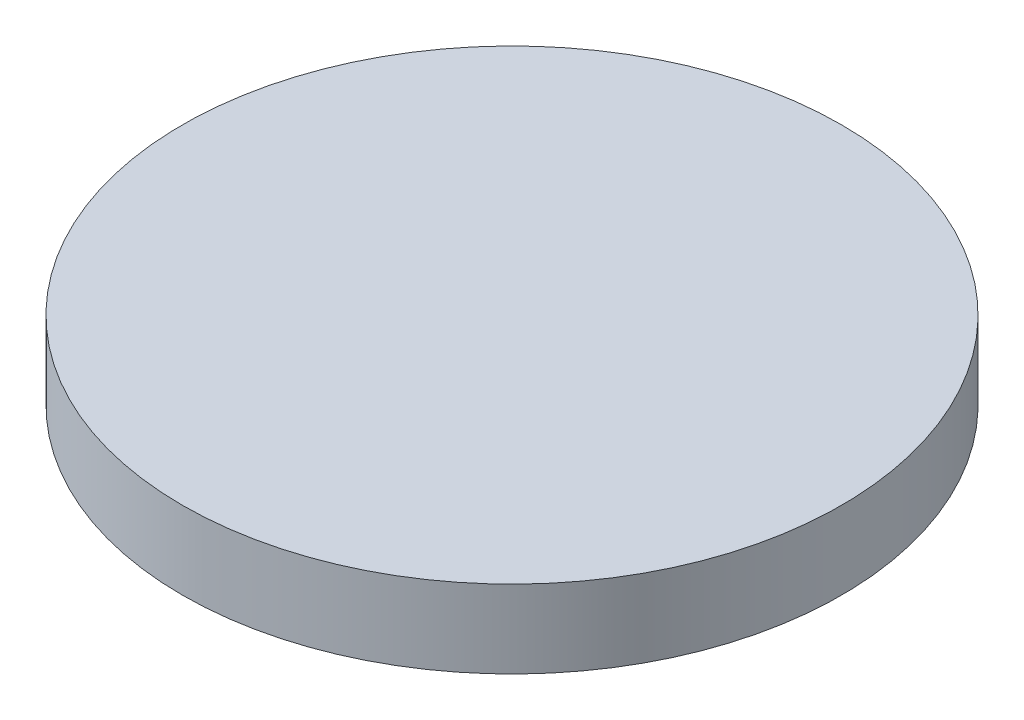
SolidWorks part; units mm, degrees
ref_plane "Front Plane" through (0, 0, 0) normal (0, 0, 1) x (1, 0, 0)
ref_plane "Top Plane" through (0, 0, 0) normal (0, 1, 0) x (1, 0, 0)
ref_plane "Right Plane" through (0, 0, 0) normal (1, 0, 0) x (0, 0, -1)
sketch "Sketch1" plane through (0, 0, 0) normal (0, 1, 0) x (1, 0, 0)
  circle A0 centre (0, 0) radius 6.35
  dimension "D1" = 12.7
extrude "Boss-Extrude1" add sketch "Sketch1" along normal blind 1.5
